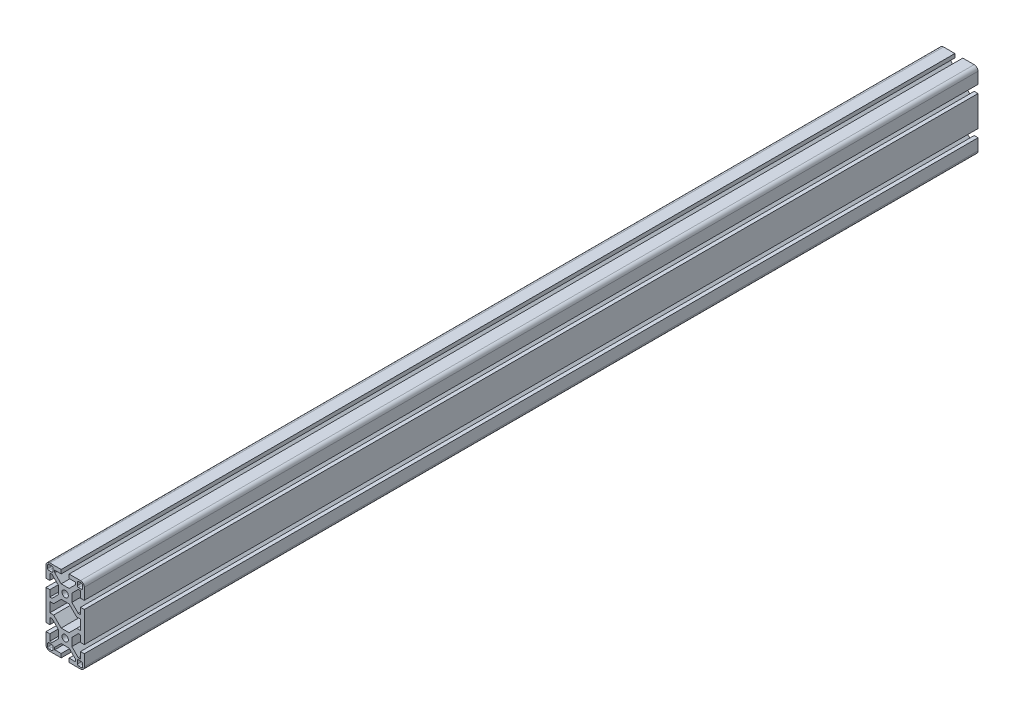
SolidWorks part; units mm, degrees
material "1060 Alloy"
ref_plane "Front" through (0, 0, 0) normal (0, 0, 1) x (1, 0, 0)
ref_plane "Top" through (0, 0, 0) normal (0, 1, 0) x (1, 0, 0)
ref_plane "Right" through (0, 0, 0) normal (1, 0, 0) x (0, 0, -1)
ref_plane "Plane1" through (0, 0, 25) normal (0, 0, 1) x (1, 0, 0)
sketch "Sketch1" plane through (0, 0, 25) normal (0, 0, 1) x (1, 0, 0)
  line L0 (-9.5, 12.7) -> (-9.5, 10.5)
  line L1 (-10.5, 9.5) -> (-12.7, 9.5)
  line L2 (-13.7, 10.5) -> (-13.7, 12.7)
  line L3 (-12.7, 13.7) -> (-10.5, 13.7)
  line L4 (12.7, 9.5) -> (10.5, 9.5)
  line L5 (9.5, 10.5) -> (9.5, 12.7)
  line L6 (10.5, 13.7) -> (12.7, 13.7)
  line L7 (13.7, 12.7) -> (13.7, 10.5)
  line L8 (-12.7, -39.5) -> (-10.5, -39.5)
  line L9 (-9.5, -40.5) -> (-9.5, -42.7)
  line L10 (-10.5, -43.7) -> (-12.7, -43.7)
  line L11 (-13.7, -42.7) -> (-13.7, -40.5)
  line L12 (9.5, -42.7) -> (9.5, -40.5)
  line L13 (10.5, -39.5) -> (12.7, -39.5)
  line L14 (13.7, -40.5) -> (13.7, -42.7)
  line L15 (12.7, -43.7) -> (10.5, -43.7)
  line L16 (0, 0) -> (-18.8009, 18.8009) construction
  line L17 (0, 0) -> (15.8468, 15.8468) construction
  line L18 (0, 0) -> (0, -54.7376) construction
  line L19 (0, -30) -> (18.7024, -48.7024) construction
  line L20 (0, -30) -> (-20.187, -50.187) construction
  line L21 (10.2713, -21.85) -> (12, -21.85)
  line L22 (12, -21.85) -> (12, -26.9)
  line L23 (3.1287, -24.75) -> (9.0287, -18.85)
  line L24 (-12, -18.85) -> (-9.0287, -18.85)
  line L26 (-11.3684, -30) -> (11.3684, -30) construction
  line L27 (9.0287, -18.85) -> (12, -18.85)
  line L33 (3.1287, -24.75) -> (-3.1287, -24.75)
  line L34 (-3.1287, -24.75) -> (-9.0287, -18.85)
  line L36 (-12, -18.85) -> (-12, -11.15)
  line L37 (-12, -11.15) -> (-9.0287, -11.15)
  line L38 (-9.0287, -11.15) -> (-3.1287, -5.25)
  line L39 (-3.1287, -5.25) -> (3.1287, -5.25)
  line L40 (3.1287, -5.25) -> (9.0287, -11.15)
  line L41 (9.0287, -11.15) -> (12, -11.15)
  line L42 (12, -11.15) -> (12, -18.85)
  line L44 (12, -26.9) -> (15, -26.9)
  line L47 (15, -26.9) -> (15, -3.1)
  line L50 (15, -3.1) -> (12, -3.1)
  line L51 (12, -3.1) -> (12, -8.15)
  line L52 (12, -8.15) -> (10.2713, -8.15)
  line L53 (10.2713, -8.15) -> (5.25, -3.1287)
  line L57 (5.25, -3.1287) -> (5.25, 3.1287)
  line L58 (5.25, 3.1287) -> (10.2713, 8.15)
  line L59 (10.2713, 8.15) -> (12, 8.15)
  line L60 (12, 8.15) -> (12, 3.1)
  line L61 (12, 3.1) -> (15, 3.1)
  line L64 (15, 3.1) -> (15, 12)
  line L65 (12, 15) -> (3.1, 15)
  line L68 (3.1, 15) -> (3.1, 12)
  line L69 (3.1, 12) -> (8.15, 12)
  line L70 (8.15, 12) -> (8.15, 10.2713)
  line L71 (8.15, 10.2713) -> (3.1287, 5.25)
  line L75 (3.1287, 5.25) -> (-3.1287, 5.25)
  line L76 (-3.1287, 5.25) -> (-8.15, 10.2713)
  line L77 (-8.15, 10.2713) -> (-8.15, 12)
  line L78 (-8.15, 12) -> (-3.1, 12)
  line L79 (-3.1, 12) -> (-3.1, 15)
  line L82 (-3.1, 15) -> (-12, 15)
  line L83 (-15, 12) -> (-15, 3.1)
  line L86 (-15, 3.1) -> (-12, 3.1)
  line L87 (-12, 3.1) -> (-12, 8.15)
  line L88 (-12, 8.15) -> (-10.2713, 8.15)
  line L89 (-10.2713, 8.15) -> (-5.25, 3.1287)
  line L93 (-5.25, 3.1287) -> (-5.25, -3.1287)
  line L94 (-5.25, -3.1287) -> (-10.2713, -8.15)
  line L95 (-10.2713, -8.15) -> (-12, -8.15)
  line L96 (-12, -8.15) -> (-12, -3.1)
  line L97 (-12, -3.1) -> (-15, -3.1)
  line L100 (-15, -3.1) -> (-15, -26.9)
  line L103 (-15, -26.9) -> (-12, -26.9)
  line L104 (-12, -26.9) -> (-12, -21.85)
  line L105 (-12, -21.85) -> (-10.2713, -21.85)
  line L106 (-10.2713, -21.85) -> (-5.25, -26.8713)
  line L110 (-5.25, -26.8713) -> (-5.25, -33.1287)
  line L111 (-5.25, -33.1287) -> (-10.2713, -38.15)
  line L112 (-10.2713, -38.15) -> (-12, -38.15)
  line L113 (-12, -38.15) -> (-12, -33.1)
  line L114 (-12, -33.1) -> (-15, -33.1)
  line L117 (-15, -33.1) -> (-15, -42)
  line L118 (-12, -45) -> (-3.1, -45)
  line L121 (-3.1, -45) -> (-3.1, -42)
  line L122 (-3.1, -42) -> (-8.15, -42)
  line L123 (-8.15, -42) -> (-8.15, -40.2713)
  line L124 (-8.15, -40.2713) -> (-3.1287, -35.25)
  line L125 (-3.1287, -35.25) -> (3.1287, -35.25)
  line L129 (3.1287, -35.25) -> (8.15, -40.2713)
  line L130 (8.15, -40.2713) -> (8.15, -42)
  line L131 (8.15, -42) -> (3.1, -42)
  line L132 (3.1, -42) -> (3.1, -45)
  line L135 (3.1, -45) -> (12, -45)
  line L136 (15, -42) -> (15, -33.1)
  line L139 (15, -33.1) -> (12, -33.1)
  line L140 (12, -33.1) -> (12, -38.15)
  line L141 (12, -38.15) -> (10.2713, -38.15)
  line L142 (10.2713, -38.15) -> (5.25, -33.1287)
  line L143 (5.25, -33.1287) -> (5.25, -26.8713)
  line L147 (5.25, -26.8713) -> (10.2713, -21.85)
  arc A0 (-9.5, 10.5) -> (-10.5, 9.5) centre (-10.5, 10.5) cw
  arc A1 (-12.7, 9.5) -> (-13.7, 10.5) centre (-12.7, 10.5) cw
  arc A2 (-13.7, 12.7) -> (-12.7, 13.7) centre (-12.7, 12.7) cw
  arc A3 (-10.5, 13.7) -> (-9.5, 12.7) centre (-10.5, 12.7) cw
  arc A4 (10.5, 9.5) -> (9.5, 10.5) centre (10.5, 10.5) cw
  arc A5 (9.5, 12.7) -> (10.5, 13.7) centre (10.5, 12.7) cw
  arc A6 (12.7, 13.7) -> (13.7, 12.7) centre (12.7, 12.7) cw
  arc A7 (13.7, 10.5) -> (12.7, 9.5) centre (12.7, 10.5) cw
  arc A8 (-10.5, -39.5) -> (-9.5, -40.5) centre (-10.5, -40.5) cw
  arc A9 (-9.5, -42.7) -> (-10.5, -43.7) centre (-10.5, -42.7) cw
  arc A10 (-12.7, -43.7) -> (-13.7, -42.7) centre (-12.7, -42.7) cw
  arc A11 (-13.7, -40.5) -> (-12.7, -39.5) centre (-12.7, -40.5) cw
  arc A12 (9.5, -40.5) -> (10.5, -39.5) centre (10.5, -40.5) cw
  arc A13 (12.7, -39.5) -> (13.7, -40.5) centre (12.7, -40.5) cw
  arc A14 (13.7, -42.7) -> (12.7, -43.7) centre (12.7, -42.7) cw
  arc A15 (10.5, -43.7) -> (9.5, -42.7) centre (10.5, -42.7) cw
  circle A16 centre (0, 0) radius 2.45
  circle A17 centre (0, -30) radius 2.45
  arc A63 (15, 12) -> (12, 15) centre (12, 12) ccw
  arc A79 (-12, 15) -> (-15, 12) centre (-12, 12) ccw
  arc A110 (-15, -42) -> (-12, -45) centre (-12, -42) ccw
  arc A126 (12, -45) -> (15, -42) centre (12, -42) ccw
  point P52 (5.25, 0)
  point P55 (-7.55, -45)
  point P165 (-13.5, 3.1)
  point P166 (-10.5143, -11.15)
  dimension "D1" = 4.9
  dimension "D2" = 15
  dimension "D4" = 3
  dimension "D14" = 3
  dimension "D32" = 30
  dimension "D33" = 4.9
  dimension "D34" = 15
  dimension "D50" = 5.25
  dimension "D54" = 3
  dimension "D55" = 5.25
  dimension "D57" = 3
  dimension "D3" = 15
  dimension "D5" = 3.1
  dimension "D6" = 3
  dimension "D7" = 9.75
  dimension "D8" = 9.75
  dimension "D9" = 15
  dimension "D10" = 9.75
  dimension "D11" = 8.15
  dimension "D12" = 16.3
  dimension "D13" = 6.2
  dimension "D15" = 45
  dimension "D16" = 45
  dimension "D17" = 1.5
  dimension "D18" = 3
  dimension "D19" = 1.5
  dimension "D20" = 3
  dimension "D21" = 3
  dimension "D22" = 3
  dimension "D23" = 3.1
  dimension "D24" = 6.2
  dimension "D25" = 8.15
  dimension "D26" = 16.3
  dimension "D27" = 3
  dimension "D28" = 3
  dimension "D29" = 3
  dimension "D30" = 3
  dimension "D31" = 3
  dimension "D35" = 1.5
  dimension "D36" = 3.1
  dimension "D37" = 3.1
  dimension "D38" = 45
  dimension "D39" = 45
  dimension "D40" = 1.5
  dimension "D41" = 1.5
  dimension "D42" = 3
  dimension "D43" = 3
  dimension "D44" = 3
  dimension "D45" = 3
  dimension "D46" = 3
  dimension "D47" = 8.15
  dimension "D48" = 5.25
  dimension "D49" = 5.25
  dimension "D51" = 3
  dimension "D52" = 5.25
  dimension "D53" = 16.3
  dimension "D56" = 3
extrude "Boss-Extrude1" add sketch "Sketch1" against normal blind 700
sketch "Sketch2" plane through (15, 0, 0) normal (1, 0, 0) x (0, 0, -1)
  line L0 (-25, -30) -> (30, -30) construction
  line L1 (-25, -3.1287) -> (-25, 3.1287) construction
  line L3 (675, 15) -> (-25, 15) construction
  line L4 (-25, 3.1) -> (-25, 12) construction
  circle A0 centre (30, -30) radius 3
  dimension "D2" = 6
  dimension "D1" = 45
  dimension "D3" = 55
extrude "Cut-Extrude1" cut sketch "Sketch2" against normal through all
hole_wizard "M6x1.0 Tapped Hole1" positions "Sketch3" profile "Sketch4" tap size "M6x1.0" standard "ANSI Metric"
sketch "Sketch3" plane through (0, 0, 25) normal (0, 0, 1) x (1, 0, 0)
  point P0 (0, 0)
  point P3 (0, -30)
sketch "Sketch4" plane through (0, 0, 25) normal (1, 0, 0) x (0, -1, 0)
  line L0 (0, 0) -> (0, 29.5022)
  line L1 (0, 29.5022) -> (2.5, 28)
  line L2 (2.5, 28) -> (2.5, 0)
  line L5 (2.5, 0) -> (0, 0)
  line L10 (0, 29.5022) -> (-2.5, 28) construction
  line L11 (0, -6.35) -> (0, 107.95) construction
  dimension "Tap Drill Dia." = 5
  dimension "Tap Drill Depth" = 28
  dimension "Drill Angle" = 118
cosmetic thread "Hole Thread1" parameters "D1"=25, "D2"=6
cosmetic thread "Hole Thread2" parameters "D1"=25, "D2"=6
hole_wizard "M6x1.0 Tapped Hole2" positions "Sketch5" profile "Sketch6" tap size "M6x1.0" standard "ANSI Metric"
sketch "Sketch5" plane through (0, 0, -675) normal (0, 0, -1) x (-1, 0, 0)
  point P0 (0, 0)
  point P3 (0, -30)
sketch "Sketch6" plane through (0, 0, -675) normal (1, 0, 0) x (0, 1, 0)
  line L0 (0, 0) -> (0, 29.5022)
  line L1 (0, 29.5022) -> (2.5, 28)
  line L2 (2.5, 28) -> (2.5, 0)
  line L5 (2.5, 0) -> (0, 0)
  line L10 (0, 29.5022) -> (-2.5, 28) construction
  line L11 (0, -6.35) -> (0, 107.95) construction
  dimension "Tap Drill Dia." = 5
  dimension "Tap Drill Depth" = 28
  dimension "Drill Angle" = 118
cosmetic thread "Hole Thread3" parameters "D1"=25, "D2"=6
cosmetic thread "Hole Thread4" parameters "D1"=25, "D2"=6
